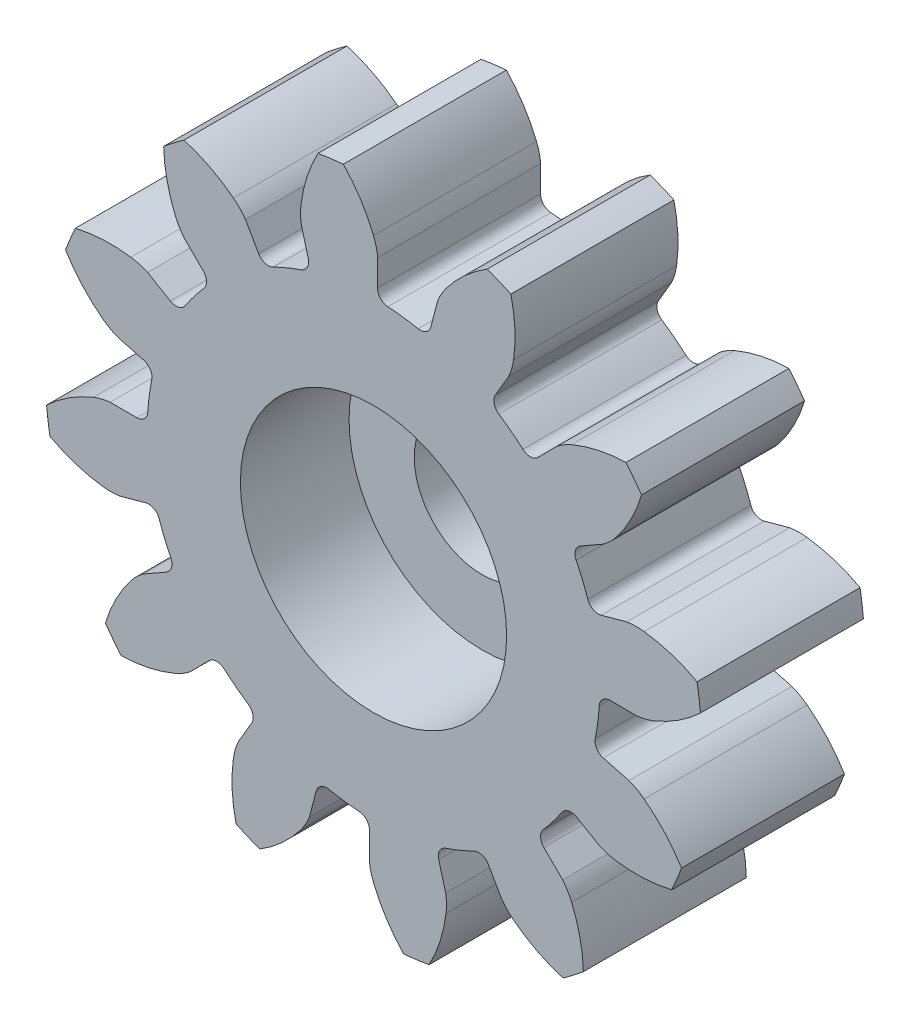
SolidWorks part; units mm, degrees
ref_plane "Front Plane" through (0, 0, 0) normal (0, 0, 1) x (1, 0, 0)
ref_plane "Top Plane" through (0, 0, 0) normal (0, 1, 0) x (1, 0, 0)
ref_plane "Right Plane" through (0, 0, 0) normal (1, 0, 0) x (0, 0, -1)
sketch "Sketch1" plane through (0, 0, 0) normal (0, 0, 1) x (1, 0, 0)
  line L48 (-1.3289, 4.6605) -> (-1.1999, 4.1898)
  line L49 (-2.1142, 3.8111) -> (-2.3558, 4.2352)
  line L50 (-3.4812, 3.3716) -> (-3.134, 3.0285)
  line L51 (-3.7365, 2.2434) -> (-4.1577, 2.4899)
  line L52 (-4.7006, 1.1794) -> (-4.2284, 1.0558)
  line L53 (-4.3576, 0.0746) -> (-4.8457, 0.0774)
  line L54 (-4.6605, -1.3289) -> (-4.1898, -1.1999)
  line L55 (-3.8111, -2.1142) -> (-4.2352, -2.3558)
  line L56 (-3.3716, -3.4812) -> (-3.0285, -3.134)
  line L57 (-2.2434, -3.7365) -> (-2.4899, -4.1577)
  line L58 (-1.1794, -4.7006) -> (-1.0558, -4.2284)
  line L59 (-0.0746, -4.3576) -> (-0.0774, -4.8457)
  line L60 (1.3289, -4.6605) -> (1.1999, -4.1898)
  line L61 (2.1142, -3.8111) -> (2.3558, -4.2352)
  line L62 (3.4812, -3.3716) -> (3.134, -3.0285)
  line L63 (3.7365, -2.2434) -> (4.1577, -2.4899)
  line L64 (4.7006, -1.1794) -> (4.2284, -1.0558)
  line L65 (4.3576, -0.0746) -> (4.8457, -0.0774)
  line L66 (4.6605, 1.3289) -> (4.1898, 1.1999)
  line L67 (3.8111, 2.1142) -> (4.2352, 2.3558)
  line L68 (3.3716, 3.4812) -> (3.0285, 3.134)
  line L69 (2.2434, 3.7365) -> (2.4899, 4.1577)
  line L70 (1.1794, 4.7006) -> (1.0558, 4.2284)
  line L71 (0.0746, 4.3576) -> (0.0774, 4.8457)
  circle A0 centre (0, 0) radius 2.45
  arc A192 (0.0002, 5.1569) -> (-0.5543, 6.0169) centre (-2.5558, 4.1176) ccw
  arc A193 (-0.5543, 6.0169) -> (-1.0218, 5.9553) centre (0, 0) ccw
  arc A194 (-1.0218, 5.9553) -> (-1.3349, 4.9811) centre (1.403, 4.6388) ccw
  arc A195 (-1.3349, 4.9811) -> (-1.3289, 4.6605) centre (-0.2176, 4.8414) ccw
  arc A196 (-1.3304, 3.9445) -> (-1.1999, 4.1898) centre (-1.3951, 4.1363) ccw
  arc A197 (-1.3304, 3.9445) -> (-1.8484, 3.7299) centre (0, 0) ccw
  arc A198 (-2.1142, 3.8111) -> (-1.8484, 3.7299) centre (-1.9383, 3.9113) ccw
  arc A199 (-2.3558, 4.2352) -> (-2.5783, 4.4661) centre (-3.2695, 3.5772) ccw
  arc A200 (-2.5783, 4.4661) -> (-3.4885, 4.9336) centre (-4.2721, 2.288) ccw
  arc A201 (-3.4885, 4.9336) -> (-3.8626, 4.6465) centre (0, 0) ccw
  arc A202 (-3.8626, 4.6465) -> (-3.6466, 3.6463) centre (-1.1044, 4.7188) ccw
  arc A203 (-3.6466, 3.6463) -> (-3.4812, 3.3716) centre (-2.6091, 4.084) ccw
  arc A204 (-3.1244, 2.7508) -> (-3.134, 3.0285) centre (-3.2763, 2.8846) ccw
  arc A205 (-3.1244, 2.7508) -> (-3.4657, 2.306) centre (0, 0) ccw
  arc A206 (-3.7365, 2.2434) -> (-3.4657, 2.306) centre (-3.6343, 2.4181) ccw
  arc A207 (-4.1577, 2.4899) -> (-4.4659, 2.5786) centre (-4.6201, 1.4632) ccw
  arc A208 (-4.4659, 2.5786) -> (-5.4879, 2.5284) centre (-4.8438, -0.1546) ccw
  arc A209 (-5.4879, 2.5284) -> (-5.6684, 2.0927) centre (0, 0) ccw
  arc A210 (-5.6684, 2.0927) -> (-4.9812, 1.3345) centre (-3.3158, 3.5344) ccw
  arc A211 (-4.9812, 1.3345) -> (-4.7006, 1.1794) centre (-4.3015, 2.2323) ccw
  arc A212 (-4.0812, 0.8201) -> (-4.2284, 1.0558) centre (-4.2797, 0.86) ccw
  arc A213 (-4.0812, 0.8201) -> (-4.1544, 0.2642) centre (0, 0) ccw
  arc A214 (-4.3576, 0.0746) -> (-4.1544, 0.2642) centre (-4.3564, 0.277) ccw
  arc A215 (-4.8457, 0.0774) -> (-5.1569, 0.0002) centre (-4.7327, -1.0429) ccw
  arc A216 (-5.1569, 0.0002) -> (-6.0169, -0.5543) centre (-4.1176, -2.5558) ccw
  arc A217 (-6.0169, -0.5543) -> (-5.9553, -1.0218) centre (0, 0) ccw
  arc A218 (-5.9553, -1.0218) -> (-4.9811, -1.3349) centre (-4.6388, 1.403) ccw
  arc A219 (-4.9811, -1.3349) -> (-4.6605, -1.3289) centre (-4.8414, -0.2176) ccw
  arc A220 (-3.9445, -1.3304) -> (-4.1898, -1.1999) centre (-4.1363, -1.3951) ccw
  arc A221 (-3.9445, -1.3304) -> (-3.7299, -1.8484) centre (0, 0) ccw
  arc A222 (-3.8111, -2.1142) -> (-3.7299, -1.8484) centre (-3.9113, -1.9383) ccw
  arc A223 (-4.2352, -2.3558) -> (-4.4661, -2.5783) centre (-3.5772, -3.2695) ccw
  arc A224 (-4.4661, -2.5783) -> (-4.9336, -3.4885) centre (-2.288, -4.2721) ccw
  arc A225 (-4.9336, -3.4885) -> (-4.6465, -3.8626) centre (0, 0) ccw
  arc A226 (-4.6465, -3.8626) -> (-3.6463, -3.6466) centre (-4.7188, -1.1044) ccw
  arc A227 (-3.6463, -3.6466) -> (-3.3716, -3.4812) centre (-4.084, -2.6091) ccw
  arc A228 (-2.7508, -3.1244) -> (-3.0285, -3.134) centre (-2.8846, -3.2763) ccw
  arc A229 (-2.7508, -3.1244) -> (-2.306, -3.4657) centre (0, 0) ccw
  arc A230 (-2.2434, -3.7365) -> (-2.306, -3.4657) centre (-2.4181, -3.6343) ccw
  arc A231 (-2.4899, -4.1577) -> (-2.5786, -4.4659) centre (-1.4632, -4.6201) ccw
  arc A232 (-2.5786, -4.4659) -> (-2.5284, -5.4879) centre (0.1546, -4.8438) ccw
  arc A233 (-2.5284, -5.4879) -> (-2.0927, -5.6684) centre (0, 0) ccw
  arc A234 (-2.0927, -5.6684) -> (-1.3345, -4.9812) centre (-3.5344, -3.3158) ccw
  arc A235 (-1.3345, -4.9812) -> (-1.1794, -4.7006) centre (-2.2323, -4.3015) ccw
  arc A236 (-0.8201, -4.0812) -> (-1.0558, -4.2284) centre (-0.86, -4.2797) ccw
  arc A237 (-0.8201, -4.0812) -> (-0.2642, -4.1544) centre (0, 0) ccw
  arc A238 (-0.0746, -4.3576) -> (-0.2642, -4.1544) centre (-0.277, -4.3564) ccw
  arc A239 (-0.0774, -4.8457) -> (-0.0002, -5.1569) centre (1.0429, -4.7327) ccw
  arc A240 (-0.0002, -5.1569) -> (0.5543, -6.0169) centre (2.5558, -4.1176) ccw
  arc A241 (0.5543, -6.0169) -> (1.0218, -5.9553) centre (0, 0) ccw
  arc A242 (1.0218, -5.9553) -> (1.3349, -4.9811) centre (-1.403, -4.6388) ccw
  arc A243 (1.3349, -4.9811) -> (1.3289, -4.6605) centre (0.2176, -4.8414) ccw
  arc A244 (1.3304, -3.9445) -> (1.1999, -4.1898) centre (1.3951, -4.1363) ccw
  arc A245 (1.3304, -3.9445) -> (1.8484, -3.7299) centre (0, 0) ccw
  arc A246 (2.1142, -3.8111) -> (1.8484, -3.7299) centre (1.9383, -3.9113) ccw
  arc A247 (2.3558, -4.2352) -> (2.5783, -4.4661) centre (3.2695, -3.5772) ccw
  arc A248 (2.5783, -4.4661) -> (3.4885, -4.9336) centre (4.2721, -2.288) ccw
  arc A249 (3.4885, -4.9336) -> (3.8626, -4.6465) centre (0, 0) ccw
  arc A250 (3.8626, -4.6465) -> (3.6466, -3.6463) centre (1.1044, -4.7188) ccw
  arc A251 (3.6466, -3.6463) -> (3.4812, -3.3716) centre (2.6091, -4.084) ccw
  arc A252 (3.1244, -2.7508) -> (3.134, -3.0285) centre (3.2763, -2.8846) ccw
  arc A253 (3.1244, -2.7508) -> (3.4657, -2.306) centre (0, 0) ccw
  arc A254 (3.7365, -2.2434) -> (3.4657, -2.306) centre (3.6343, -2.4181) ccw
  arc A255 (4.1577, -2.4899) -> (4.4659, -2.5786) centre (4.6201, -1.4632) ccw
  arc A256 (4.4659, -2.5786) -> (5.4879, -2.5284) centre (4.8438, 0.1546) ccw
  arc A257 (5.4879, -2.5284) -> (5.6684, -2.0927) centre (0, 0) ccw
  arc A258 (5.6684, -2.0927) -> (4.9812, -1.3345) centre (3.3158, -3.5344) ccw
  arc A259 (4.9812, -1.3345) -> (4.7006, -1.1794) centre (4.3015, -2.2323) ccw
  arc A260 (4.0812, -0.8201) -> (4.2284, -1.0558) centre (4.2797, -0.86) ccw
  arc A261 (4.0812, -0.8201) -> (4.1544, -0.2642) centre (0, 0) ccw
  arc A262 (4.3576, -0.0746) -> (4.1544, -0.2642) centre (4.3564, -0.277) ccw
  arc A263 (4.8457, -0.0774) -> (5.1569, -0.0002) centre (4.7327, 1.0429) ccw
  arc A264 (5.1569, -0.0002) -> (6.0169, 0.5543) centre (4.1176, 2.5558) ccw
  arc A265 (6.0169, 0.5543) -> (5.9553, 1.0218) centre (0, 0) ccw
  arc A266 (5.9553, 1.0218) -> (4.9811, 1.3349) centre (4.6388, -1.403) ccw
  arc A267 (4.9811, 1.3349) -> (4.6605, 1.3289) centre (4.8414, 0.2176) ccw
  arc A268 (3.9445, 1.3304) -> (4.1898, 1.1999) centre (4.1363, 1.3951) ccw
  arc A269 (3.9445, 1.3304) -> (3.7299, 1.8484) centre (0, 0) ccw
  arc A270 (3.8111, 2.1142) -> (3.7299, 1.8484) centre (3.9113, 1.9383) ccw
  arc A271 (4.2352, 2.3558) -> (4.4661, 2.5783) centre (3.5772, 3.2695) ccw
  arc A272 (4.4661, 2.5783) -> (4.9336, 3.4885) centre (2.288, 4.2721) ccw
  arc A273 (4.9336, 3.4885) -> (4.6465, 3.8626) centre (0, 0) ccw
  arc A274 (4.6465, 3.8626) -> (3.6463, 3.6466) centre (4.7188, 1.1044) ccw
  arc A275 (3.6463, 3.6466) -> (3.3716, 3.4812) centre (4.084, 2.6091) ccw
  arc A276 (2.7508, 3.1244) -> (3.0285, 3.134) centre (2.8846, 3.2763) ccw
  arc A277 (2.7508, 3.1244) -> (2.306, 3.4657) centre (0, 0) ccw
  arc A278 (2.2434, 3.7365) -> (2.306, 3.4657) centre (2.4181, 3.6343) ccw
  arc A279 (2.4899, 4.1577) -> (2.5786, 4.4659) centre (1.4632, 4.6201) ccw
  arc A280 (2.5786, 4.4659) -> (2.5284, 5.4879) centre (-0.1546, 4.8438) ccw
  arc A281 (2.5284, 5.4879) -> (2.0927, 5.6684) centre (0, 0) ccw
  arc A282 (2.0927, 5.6684) -> (1.3345, 4.9812) centre (3.5344, 3.3158) ccw
  arc A283 (1.3345, 4.9812) -> (1.1794, 4.7006) centre (2.2323, 4.3015) ccw
  arc A284 (0.8201, 4.0812) -> (1.0558, 4.2284) centre (0.86, 4.2797) ccw
  arc A285 (0.8201, 4.0812) -> (0.2642, 4.1544) centre (0, 0) ccw
  arc A286 (0.0746, 4.3576) -> (0.2642, 4.1544) centre (0.277, 4.3564) ccw
  arc A287 (0.0774, 4.8457) -> (0.0002, 5.1569) centre (-1.0429, 4.7327) ccw
  dimension "D1" = 4.9
extrude "Boss-Extrude1" add sketch "Sketch1" along normal blind 2 and the other way blind 1
sketch "Sketch2" plane through (0, 0, -1) normal (0, 0, -1) x (-1, 0, 0)
  circle A0 centre (0, 0) radius 2.45
  circle A2 centre (0, 0) radius 1.25
  circle A4 centre (0, 0) radius 2.45 construction
  dimension "D2" = 2.5
extrude "Boss-Extrude2" add sketch "Sketch2" against normal blind 1
